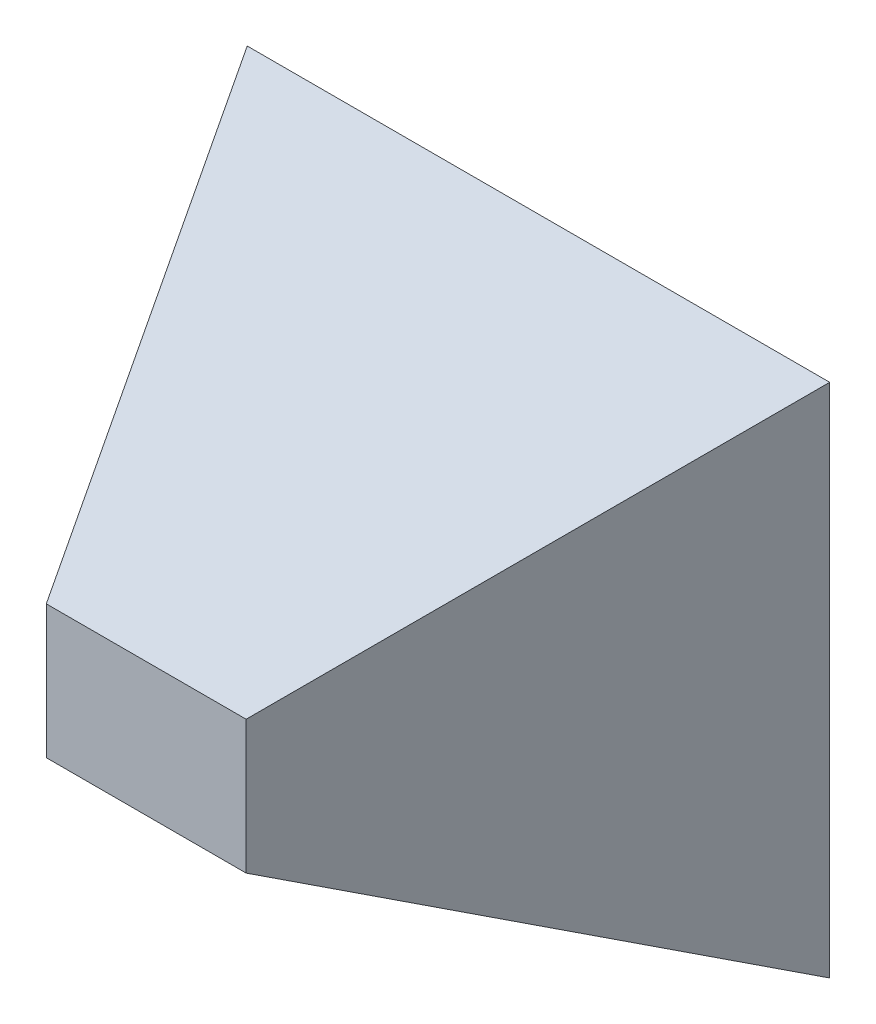
SolidWorks part; units mm, degrees
ref_plane "Front Plane" through (0, 0, 0) normal (0, 0, 1) x (1, 0, 0)
ref_plane "Top Plane" through (0, 0, 0) normal (0, 1, 0) x (1, 0, 0)
ref_plane "Right Plane" through (0, 0, 0) normal (1, 0, 0) x (0, 0, -1)
sketch "Sketch1" plane through (0, 0, 0) normal (0, 0, 1) x (1, 0, 0)
  line L1 (175, -155) -> (-175, -155)
  line L2 (175, -155) -> (175, 155)
  line L3 (175, 155) -> (-175, 155)
  line L4 (-175, -155) -> (-175, 155)
  line L5 (175, -155) -> (-175, 155) construction
  line L6 (175, 155) -> (-175, -155) construction
  point P0 (0, 0)
  dimension "D1" = 350
  dimension "D2" = 310
extrude "Boss-Extrude1" add sketch "Sketch1" along normal blind 235.7 draft 26
shell "Shell1" thickness 1
sketch "Sketch3" plane through (0, 0, 0) normal (0, 0, -1) x (-1, 0, 0)
  line L0 (-173, 153) -> (173, 153)
  line L1 (173, 153) -> (173, -153)
  line L2 (173, -153) -> (-173, -153)
  line L3 (-173, -153) -> (-173, 153)
  line L4 (-175, 155) -> (175, 155) construction
  line L5 (175, 155) -> (175, -155) construction
  line L6 (175, -155) -> (-175, -155) construction
  line L7 (-175, -155) -> (-175, 155) construction
  dimension "D1" = 2
  dimension "D2" = 2
  dimension "D3" = 2
  dimension "D4" = 2
extrude "Cut-Extrude1" cut sketch "Sketch3" against normal blind 2
